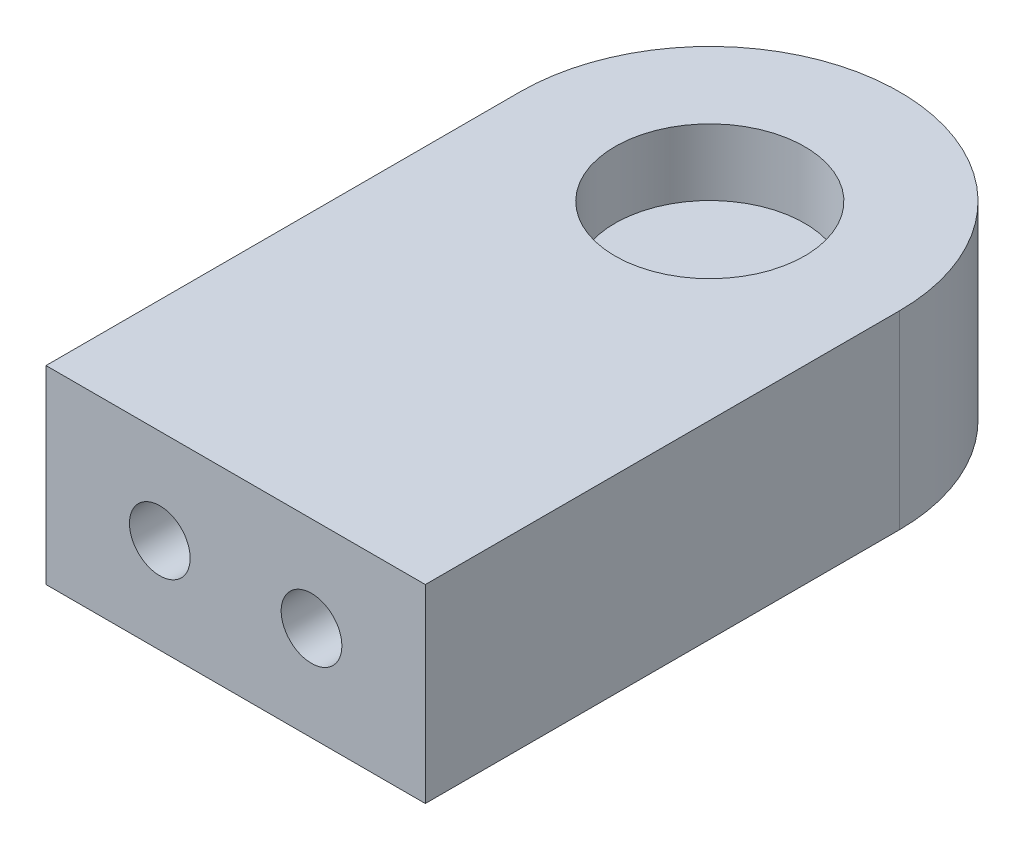
SolidWorks part; units mm, degrees
ref_plane "前视基准面" through (0, 0, 0) normal (0, 0, 1) x (1, 0, 0)
ref_plane "上视基准面" through (0, 0, 0) normal (0, 1, 0) x (1, 0, 0)
ref_plane "右视基准面" through (0, 0, 0) normal (1, 0, 0) x (0, 0, -1)
sketch "草图1" plane through (0, 0, 0) normal (0, 1, 0) x (1, 0, 0)
  line L0 (0, 0) -> (0, 25)
  line L2 (20, 25) -> (20, 0)
  line L3 (20, 0) -> (0, 0)
  arc A0 (20, 25) -> (0, 25) centre (10, 25) ccw
extrude "凸台-拉伸1" add sketch "草图1" along normal blind 10
sketch "草图2" plane through (0, 0, 0) normal (0, 1, 0) x (1, 0, 0)
  circle A0 centre (10, 25) radius 5
extrude "切除-拉伸1" cut sketch "草图2" along normal blind 3.5
ref_plane "基准面1" through (0, 10, 0) normal (0, 1, 0) x (1, 0, 0)
sketch "草图3" plane through (0, 10, 0) normal (0, 1, 0) x (1, 0, 0)
  circle A0 centre (10, 25) radius 5
extrude "切除-拉伸2" cut sketch "草图3" against normal blind 3.5
sketch "草图4" plane through (0, 0, 0) normal (0, 0, 1) x (1, 0, 0)
  circle A0 centre (6, 5) radius 1.6
  circle A1 centre (14, 5) radius 1.6
extrude "切除-拉伸3" cut sketch "草图4" against normal blind 10
cosmetic thread "装饰螺纹线1" parameters "D1"=10, "D2"=4
cosmetic thread "装饰螺纹线2" parameters "D1"=10, "D2"=4
